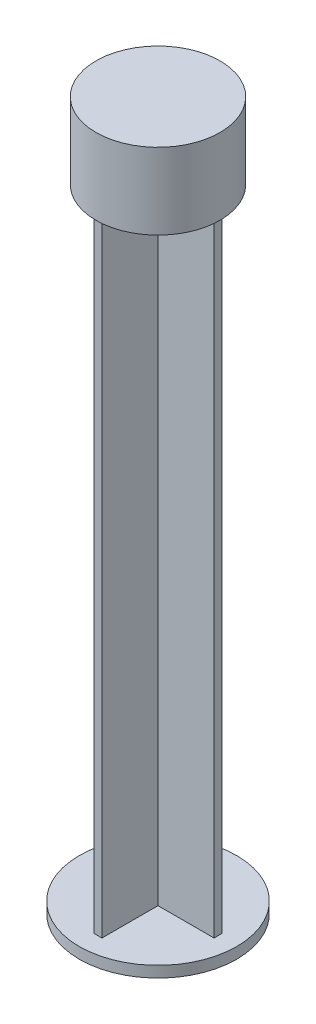
SolidWorks part; units mm, degrees
ref_plane "Front Plane" through (0, 0, 0) normal (0, 0, 1) x (1, 0, 0)
ref_plane "Top Plane" through (0, 0, 0) normal (0, 1, 0) x (1, 0, 0)
ref_plane "Right Plane" through (0, 0, 0) normal (1, 0, 0) x (0, 0, -1)
sketch "Sketch1" plane through (0, 0, 0) normal (0, 1, 0) x (1, 0, 0)
  circle A0 centre (0, 0) radius 19.675
  dimension "D1" = 39.35
extrude "Boss-Extrude1" add sketch "Sketch1" along normal blind 2.76
sketch "Sketch2" plane through (0, 2.76, 0) normal (0, 1, 0) x (1, 0, 0)
  line L1 (-1, -15) -> (1, -15)
  line L2 (-1, -15) -> (-1, 15)
  line L3 (-1, 15) -> (1, 15)
  line L4 (1, -15) -> (1, 15)
  line L5 (-1, -15) -> (1, 15) construction
  line L6 (-1, 15) -> (1, -15) construction
  line L7 (15, -1) -> (-15, -1)
  line L8 (15, -1) -> (15, 1)
  line L9 (15, 1) -> (-15, 1)
  line L10 (-15, -1) -> (-15, 1)
  line L11 (15, -1) -> (-15, 1) construction
  line L12 (15, 1) -> (-15, -1) construction
  point P0 (0, 0)
  point P6 (0, 0)
  dimension "D1" = 2
  dimension "D2" = 2
  dimension "D3" = 30
  dimension "D4" = 30
extrude "Boss-Extrude2" add sketch "Sketch2" along normal blind 155 contours L9 L4 L3 L2 | L8 L9 L4 L7 | L4 L9 L2 L7 | L4 L7 L2 L1 | L10 L7 L2 L9
sketch "Sketch3" plane through (0, 157.76, 0) normal (0, 1, 0) x (1, 0, 0)
  circle A0 centre (0, 0) radius 15.5
  dimension "D1" = 31
extrude "Boss-Extrude3" add sketch "Sketch3" along normal blind 19
